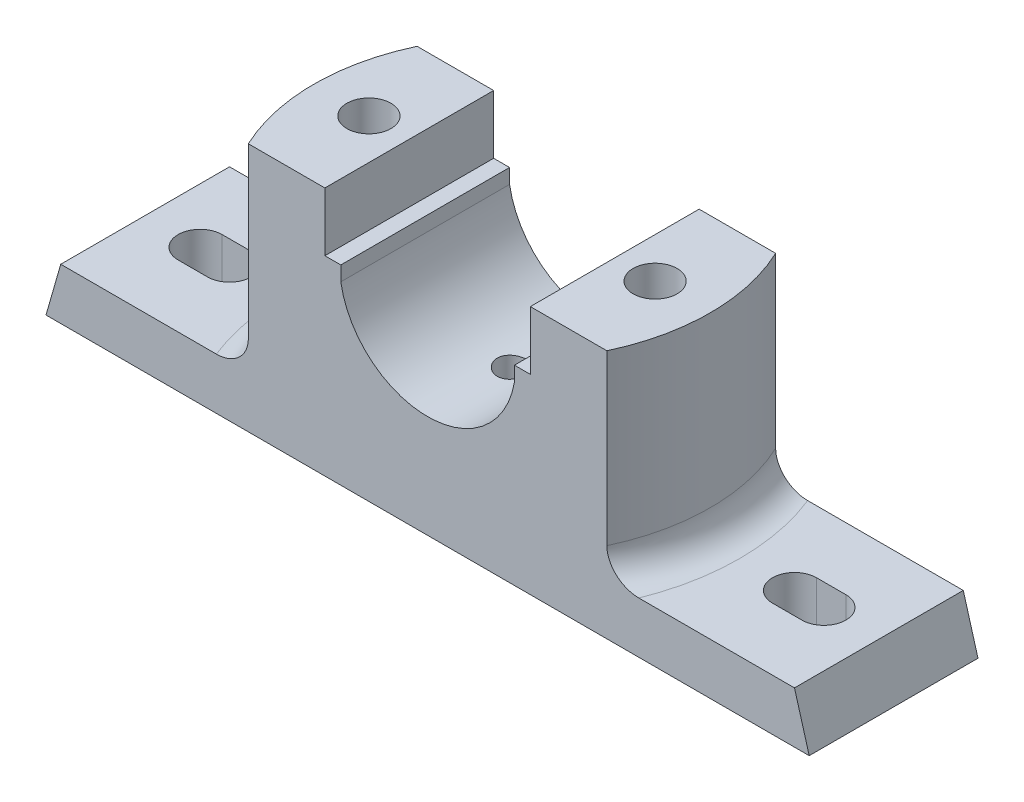
SolidWorks part; units mm, degrees
ref_plane "Front Plane" through (0, 0, 0) normal (0, 0, 1) x (1, 0, 0)
ref_plane "Top Plane" through (0, 0, 0) normal (0, 1, 0) x (1, 0, 0)
ref_plane "Right Plane" through (0, 0, 0) normal (1, 0, 0) x (0, 0, -1)
sketch "Sketch1" plane through (0, 0, 0) normal (0, 0, 1) x (1, 0, 0)
  line L0 (0, 0) -> (0, 69.6364) construction
  line L1 (104, 0) -> (-104, 0)
  line L2 (-104, 0) -> (-99.9856, 14)
  line L3 (-99.9856, 14) -> (99.9856, 14)
  line L4 (104, 0) -> (99.9856, 14)
  point P8 (0, 14)
  dimension "D1" = 104
  dimension "D2" = 106
  dimension "D3" = 14
  dimension "D4" = 208
extrude "Boss-Extrude1" add sketch "Sketch1" along normal mid plane 46
sketch "Sketch2" plane through (0, 14, 0) normal (0, 1, 0) x (1, 0, 0)
  line L4 (99.9856, 23) -> (-99.9856, 23)
  line L5 (-99.9856, 23) -> (-99.9856, -23)
  line L6 (-99.9856, -23) -> (99.9856, -23)
  line L7 (99.9856, -23) -> (99.9856, 23)
  line L8 (48.8569, 23) -> (-48.8569, 23)
  line L10 (-48.8569, -23) -> (48.8569, -23)
  arc A0 (-48.8569, 23) -> (-48.8569, -23) centre (0, 0) ccw
  arc A1 (48.8569, -23) -> (48.8569, 23) centre (0, 0) ccw
  dimension "D1" = 108
  dimension "D2" = 0
extrude "Boss-Extrude2" add sketch "Sketch2" along normal blind 68 from surface at -14 starting at face at (0, 0, 0)
sketch "Sketch3" plane through (0, 0, 0) normal (0, 0, 1) x (1, 0, 0)
  line L0 (0, 0) -> (0, 68) construction
  line L1 (-48.8569, 68) -> (48.8569, 68) construction
  line L2 (-28, 68) -> (-28, 52)
  line L3 (-28, 52) -> (-23.6611, 52)
  line L4 (-23.6611, 52) -> (-23.6611, 48)
  line L5 (23.6611, 52) -> (23.6611, 48)
  line L6 (28, 52) -> (23.6611, 52)
  line L7 (28, 68) -> (28, 52)
  line L8 (-28, 68) -> (28, 68)
  arc A0 (23.6611, 48) -> (-23.6611, 48) centre (0, 52.019) cw
  dimension "D2" = 24
  dimension "D1" = 56
  dimension "D3" = 16
  dimension "D4" = 4
extrude "Cut-Extrude1" cut sketch "Sketch3" against normal mid plane 68
sketch "Sketch4" plane through (0, 68, 0) normal (0, 1, 0) x (1, 0, 0)
  line L0 (0, 0) -> (0, 32.4313) construction
  circle A0 centre (-39, 0) radius 6
  circle A1 centre (39, 0) radius 6
  dimension "D2" = 12
  dimension "D1" = 39
extrude "Cut-Extrude2" cut sketch "Sketch4" against normal through all
sketch "Sketch5" plane through (0, 0, 0) normal (0, -1, 0) x (1, 0, 0)
  line L0 (0, 0) -> (0, 29.0886) construction
  line L1 (-53, -14) -> (-25, -14)
  line L2 (-53, -14) -> (-53, 14)
  line L3 (-53, 14) -> (-25, 14)
  line L4 (-25, -14) -> (-25, 14)
  line L5 (-53, -14) -> (-25, 14) construction
  line L6 (-53, 14) -> (-25, -14) construction
  line L7 (53, 14) -> (25, 14)
  line L8 (25, -14) -> (25, 14)
  line L9 (53, -14) -> (25, -14)
  line L10 (53, -14) -> (53, 14)
  circle A0 centre (-39, 0) radius 6 construction
  point P0 (-39, 0)
  dimension "D1" = 28
  dimension "D2" = 28
extrude "Cut-Extrude3" cut sketch "Sketch5" against normal blind 10
sketch "Sketch6" plane through (0, 0, 0) normal (0, 0, 1) x (1, 0, 0)
  line L0 (-97.5, 0) -> (-96.9265, 2)
  line L1 (-104, 0) -> (104, 0) construction
  line L2 (-96.9265, 2) -> (96.9265, 2)
  line L4 (97.5, 0) -> (-97.5, 0)
  line L5 (-99.9856, 14) -> (-104, 0) construction
  line L6 (0, 0) -> (0, 33.105) construction
  line L7 (97.5, 0) -> (96.9265, 2)
  point P8 (0, 7.8203)
  point P14 (0, 2)
  dimension "D1" = 2
  dimension "D2" = 97.5
extrude "Cut-Extrude4" cut sketch "Sketch6" against normal mid plane 32
sketch "Sketch7" plane through (0, 14, 0) normal (0, 1, 0) x (1, 0, 0)
  line L0 (-85, 0) -> (-77, 0) construction
  line L1 (-85, 6) -> (-77, 6)
  line L2 (-85, -6) -> (-77, -6)
  line L3 (0, 0) -> (0, 35.7133) construction
  line L4 (85, 0) -> (77, 0) construction
  line L5 (85, 6) -> (77, 6)
  line L6 (85, -6) -> (77, -6)
  arc A0 (-85, 6) -> (-85, -6) centre (-85, 0) ccw
  arc A1 (-77, -6) -> (-77, 6) centre (-77, 0) ccw
  arc A2 (85, 6) -> (85, -6) centre (85, 0) cw
  arc A3 (77, -6) -> (77, 6) centre (77, 0) cw
  point P3 (-81, 0)
  point P13 (81, 0)
  dimension "D3" = 6
  dimension "D4" = 6
  dimension "D1" = 8
  dimension "D2" = 77
  dimension "D5" = 77
extrude "Cut-Extrude5" cut sketch "Sketch7" against normal through all
sketch "Sketch8" plane through (0, 0, 0) normal (0, 0, 1) x (1, 0, 0)
  line L3 (4, 22.4225) -> (0, 20.019)
  line L4 (0, 28.019) -> (0, 20.019)
  line L5 (0, 28.019) -> (0, 30.4225)
  line L6 (0, 30.4225) -> (4, 30.4225)
  line L7 (4, 30.4225) -> (4, 22.4225)
  line L8 (0, 28.019) -> (0, 16.1569) construction
  arc A0 (-23.6611, 48) -> (23.6611, 48) centre (0, 52.019) ccw construction
  dimension "D1" = 4
  dimension "D2" = 4
  dimension "D3" = 8
  dimension "D4" = 8
  dimension "D5" = 59
revolve "Cut-Revolve1" cut sketch "Sketch8" angle 360 about L8
fillet "Fillet1" radius 8 2 edges at (-54, 14, 0) (54, 14, 0)
